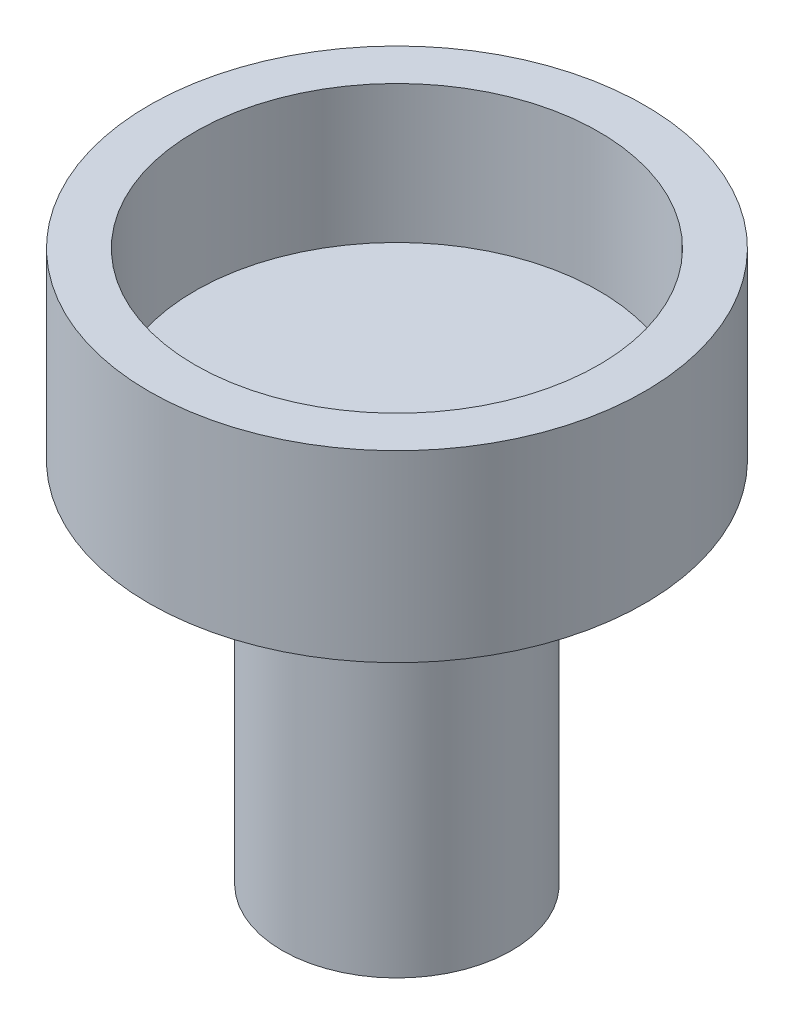
SolidWorks part; units mm, degrees
material "Natural Rubber"
ref_plane "Front Plane" through (0, 0, 0) normal (0, 0, 1) x (1, 0, 0)
ref_plane "Top Plane" through (0, 0, 0) normal (0, 1, 0) x (1, 0, 0)
ref_plane "Right Plane" through (0, 0, 0) normal (1, 0, 0) x (0, 0, -1)
sketch "BottomBaseS" plane through (0, 0, 0) normal (0, 1, 0) x (1, 0, 0)
  circle A0 centre (0, 0) radius 1.25
  dimension "Dia" = 2.5
extrude "BOTTOM BASE" add sketch "BottomBaseS" against normal blind 4
sketch "MainBaseS" plane through (0, 0, 0) normal (0, 1, 0) x (1, 0, 0)
  circle A0 centre (0, 0) radius 2.7
  circle A1 centre (0, 0) radius 1.25 construction
  dimension "RefDiaBase" = 5.4
  dimension "BaseDiaControl" = 1.45
extrude "MAIN BASE" add sketch "MainBaseS" along normal blind 0.5
sketch "WallS" plane through (0, 0.5, 0) normal (0, 1, 0) x (1, 0, 0)
  circle A0 centre (0, 0) radius 2.7
  circle A1 centre (0, 0) radius 2.2
  circle A2 centre (0, 0) radius 2.7 construction
  dimension "Thickness" = 0.5
extrude "WALL" add sketch "WallS" along normal offset from surface (1.5 mm away) 2 up to face at (0, 0, 1.25)
